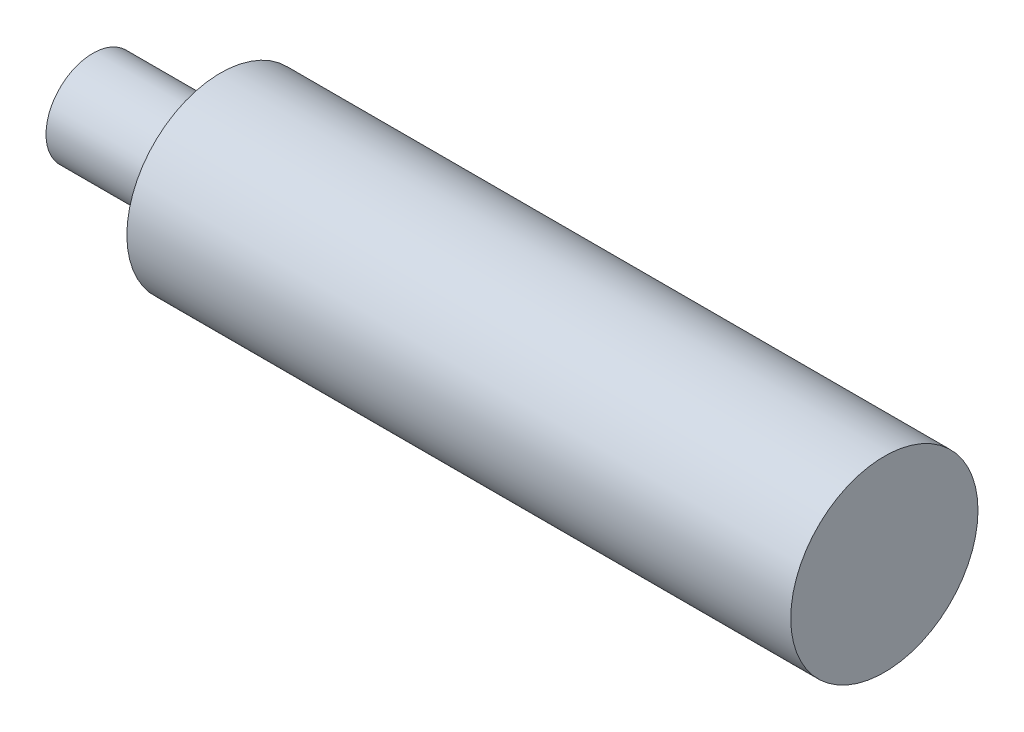
SolidWorks part; units mm, degrees
ref_plane "Front Plane" through (0, 0, 0) normal (0, 0, 1) x (1, 0, 0)
ref_plane "Top Plane" through (0, 0, 0) normal (0, 1, 0) x (1, 0, 0)
ref_plane "Right Plane" through (0, 0, 0) normal (1, 0, 0) x (0, 0, -1)
sketch "Sketch1" plane through (0, 0, 0) normal (1, 0, 0) x (0, 0, -1)
  circle A0 centre (0, 0) radius 55.88
  dimension "D1" = 111.76
extrude "Boss-Extrude1" add sketch "Sketch1" along normal mid plane 472.44
sketch "Sketch2" plane through (-236.22, 0, 0) normal (-1, 0, 0) x (0, 0, 1)
  circle A0 centre (0, 0) radius 27.94
  dimension "D1" = 55.88
extrude "Cut-Extrude1" cut sketch "Sketch2" against normal blind 76.2 flip side to cut
